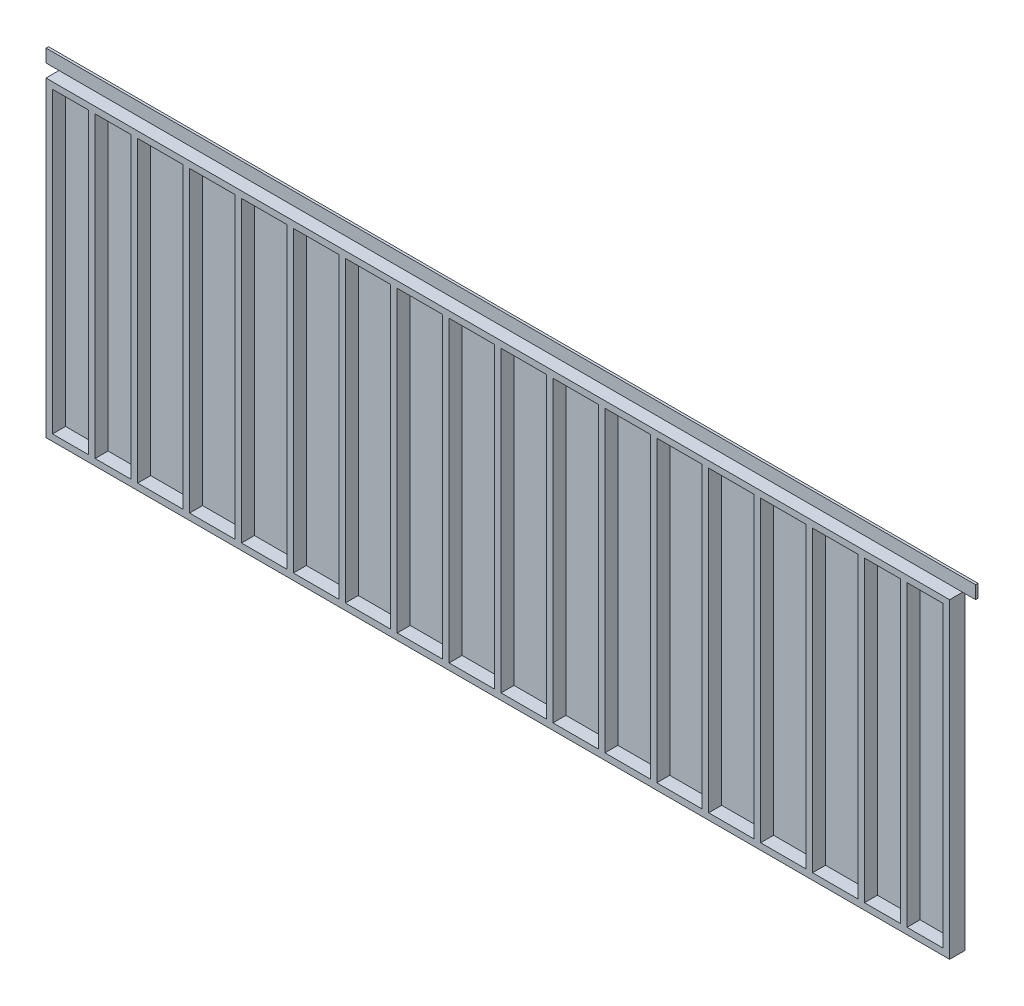
SolidWorks part; units mm, degrees
ref_plane "Front Plane" through (0, 0, 0) normal (0, 0, 1) x (1, 0, 0)
ref_plane "Top Plane" through (0, 0, 0) normal (0, 1, 0) x (1, 0, 0)
ref_plane "Right Plane" through (0, 0, 0) normal (1, 0, 0) x (0, 0, -1)
sketch "Sketch1" plane through (0, 0, 0) normal (0, 0, 1) x (1, 0, 0)
  line L0 (0, 0) -> (3536.95, 0)
  line L1 (3536.95, 0) -> (3536.95, 2438.4)
  line L2 (3536.95, 2438.4) -> (-3536.95, 2438.4)
  line L3 (-3536.95, 2438.4) -> (-3536.95, 0)
  line L4 (-3536.95, 0) -> (0, 0)
  line L5 (25.4, 2387.6) -> (25.4, 50.8)
  line L6 (-25.4, 2387.6) -> (-25.4, 50.8)
  line L7 (431.8, 2387.6) -> (431.8, 50.8)
  line L8 (381, 2387.6) -> (381, 50.8)
  line L9 (838.2, 2387.6) -> (838.2, 50.8)
  line L10 (-3486.15, 2387.6) -> (-3203.575, 2387.6)
  line L11 (-3486.15, 2387.6) -> (-3486.15, 50.8)
  line L12 (-3486.15, 50.8) -> (-3203.575, 50.8)
  line L13 (3486.15, 2387.6) -> (3486.15, 50.8)
  line L14 (787.4, 2387.6) -> (787.4, 50.8)
  line L15 (1244.6, 2387.6) -> (1244.6, 50.8)
  line L16 (1193.8, 2387.6) -> (1193.8, 50.8)
  line L17 (1651, 2387.6) -> (1651, 50.8)
  line L18 (1600.2, 2387.6) -> (1600.2, 50.8)
  line L19 (2057.4, 2387.6) -> (2057.4, 50.8)
  line L20 (2006.6, 2387.6) -> (2006.6, 50.8)
  line L21 (2463.8, 2387.6) -> (2463.8, 50.8)
  line L22 (2413, 2387.6) -> (2413, 50.8)
  line L23 (2870.2, 2387.6) -> (2870.2, 50.8)
  line L24 (2819.4, 2387.6) -> (2819.4, 50.8)
  line L25 (2870.2, 50.8) -> (3152.775, 50.8)
  line L26 (2463.8, 50.8) -> (2819.4, 50.8)
  line L27 (-381, 2387.6) -> (-381, 50.8)
  line L28 (-431.8, 2387.6) -> (-431.8, 50.8)
  line L29 (-787.4, 2387.6) -> (-787.4, 50.8)
  line L30 (-838.2, 2387.6) -> (-838.2, 50.8)
  line L31 (-1193.8, 2387.6) -> (-1193.8, 50.8)
  line L32 (-1244.6, 2387.6) -> (-1244.6, 50.8)
  line L33 (-1600.2, 2387.6) -> (-1600.2, 50.8)
  line L34 (-1651, 2387.6) -> (-1651, 50.8)
  line L35 (-2006.6, 2387.6) -> (-2006.6, 50.8)
  line L36 (-2057.4, 2387.6) -> (-2057.4, 50.8)
  line L37 (-2413, 2387.6) -> (-2413, 50.8)
  line L38 (-2463.8, 2387.6) -> (-2463.8, 50.8)
  line L39 (-2819.4, 2387.6) -> (-2819.4, 50.8)
  line L40 (-2870.2, 2387.6) -> (-2870.2, 50.8)
  line L41 (-2819.4, 2387.6) -> (-2463.8, 2387.6)
  line L42 (-2413, 2387.6) -> (-2057.4, 2387.6)
  line L43 (-3276.6, 2387.6) -> (-3276.6, 50.8) [skipped]
  line L44 (-3225.8, 2387.6) -> (-3225.8, 50.8) [skipped]
  line L45 (-2006.6, 2387.6) -> (-1651, 2387.6)
  line L46 (-1600.2, 2387.6) -> (-1244.6, 2387.6)
  line L47 (-1193.8, 2387.6) -> (-838.2, 2387.6)
  line L48 (-787.4, 2387.6) -> (-431.8, 2387.6)
  line L49 (-381, 2387.6) -> (-25.4, 2387.6)
  line L50 (25.4, 2387.6) -> (381, 2387.6)
  line L51 (431.8, 2387.6) -> (787.4, 2387.6)
  line L52 (838.2, 2387.6) -> (1193.8, 2387.6)
  line L53 (1244.6, 2387.6) -> (1600.2, 2387.6)
  line L54 (1651, 2387.6) -> (2006.6, 2387.6)
  line L55 (2057.4, 2387.6) -> (2413, 2387.6)
  line L56 (2463.8, 2387.6) -> (2819.4, 2387.6)
  line L57 (2870.2, 2387.6) -> (3152.775, 2387.6)
  line L58 (3276.6, 2387.6) -> (3276.6, 50.8) [skipped]
  line L59 (3225.8, 2387.6) -> (3225.8, 50.8) [skipped]
  line L60 (2057.4, 50.8) -> (2413, 50.8)
  line L61 (1651, 50.8) -> (2006.6, 50.8)
  line L62 (1244.6, 50.8) -> (1600.2, 50.8)
  line L63 (838.2, 50.8) -> (1193.8, 50.8)
  line L64 (431.8, 50.8) -> (787.4, 50.8)
  line L65 (25.4, 50.8) -> (381, 50.8)
  line L66 (-381, 50.8) -> (-25.4, 50.8)
  line L67 (-787.4, 50.8) -> (-431.8, 50.8)
  line L68 (-1193.8, 50.8) -> (-838.2, 50.8)
  line L69 (-1600.2, 50.8) -> (-1244.6, 50.8)
  line L70 (-2006.6, 50.8) -> (-1651, 50.8)
  line L71 (-2413, 50.8) -> (-2057.4, 50.8)
  line L72 (-2819.4, 50.8) -> (-2463.8, 50.8)
  line L73 (-3152.775, 50.8) -> (-3152.775, 2387.6)
  line L74 (-3203.575, 2387.6) -> (-3203.575, 50.8)
  line L75 (-3152.775, 2387.6) -> (-2870.2, 2387.6)
  line L76 (-3152.775, 50.8) -> (-2870.2, 50.8)
  line L77 (3203.575, 2387.6) -> (3203.575, 50.8)
  line L78 (3152.775, 50.8) -> (3152.775, 2387.6)
  line L79 (3203.575, 2387.6) -> (3486.15, 2387.6)
  line L80 (3203.575, 50.8) -> (3486.15, 50.8)
  dimension "D1" = 9
  dimension "D2" = 9
extrude "Boss-Extrude1" add sketch "Sketch1" along normal blind 101.6
sketch "Sketch2" plane through (0, 0, 0) normal (0, 0, -1) x (-1, 0, 0)
  line L1 (-3536.95, 2438.4) -> (3536.95, 2438.4)
  line L2 (-3536.95, 2438.4) -> (-3536.95, 0)
  line L3 (-3536.95, 0) -> (3536.95, 0)
  line L4 (3536.95, 2438.4) -> (3536.95, 0)
extrude "Boss-Extrude2" add sketch "Sketch2" along normal blind 19.05
sketch "Sketch3" plane through (0, 0, -19.05) normal (0, 0, -1) x (-1, 0, 0)
  line L0 (-3536.95, 2438.4) -> (-3638.55, 2438.4)
  line L1 (-3638.55, 2438.4) -> (-3638.55, 2540)
  line L2 (-3536.95, 2438.4) -> (3536.95, 2438.4)
  line L3 (3536.95, 2438.4) -> (3638.55, 2438.4)
  line L4 (3638.55, 2438.4) -> (3638.55, 2540)
  line L5 (3638.55, 2540) -> (-3638.55, 2540)
extrude "Boss-Extrude3" add sketch "Sketch3" against normal blind 19.05
